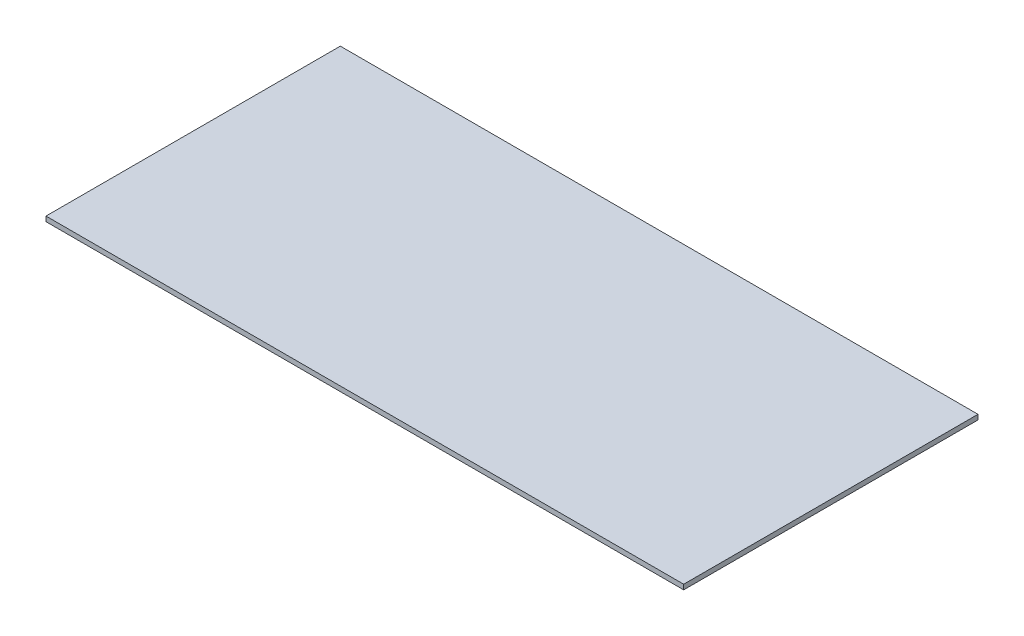
SolidWorks part; units mm, degrees
ref_plane "Front Plane" through (0, 0, 0) normal (0, 0, 1) x (1, 0, 0)
ref_plane "Top Plane" through (0, 0, 0) normal (0, 1, 0) x (1, 0, 0)
ref_plane "Right Plane" through (0, 0, 0) normal (1, 0, 0) x (0, 0, -1)
sketch "Sketch1" plane through (0, 0, 0) normal (0, 1, 0) x (1, 0, 0)
  line L1 (0, 0) -> (-65, 0)
  line L2 (0, 0) -> (0, -30)
  line L3 (0, -30) -> (-65, -30)
  line L4 (-65, 0) -> (-65, -30)
extrude "Boss-Extrude1" add sketch "Sketch1" along normal blind 0.5
